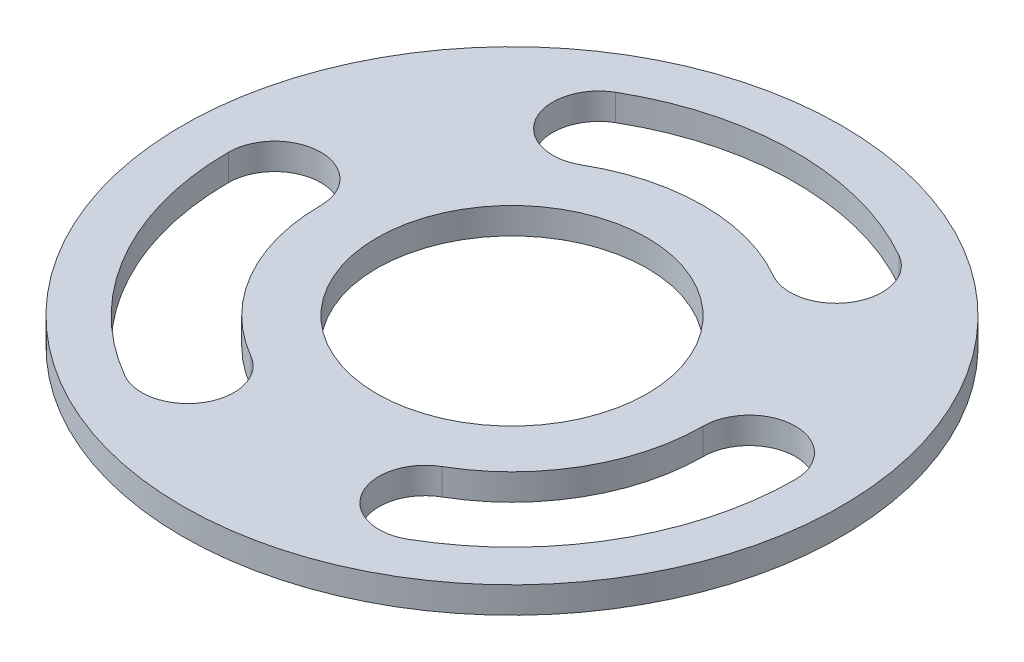
SolidWorks part; units mm, degrees
ref_plane "Alzado" through (0, 0, 0) normal (0, 0, 1) x (1, 0, 0)
ref_plane "Planta" through (0, 0, 0) normal (0, 1, 0) x (1, 0, 0)
ref_plane "Vista lateral" through (0, 0, 0) normal (1, 0, 0) x (0, 0, -1)
sketch "Croquis1" plane through (0, 0, 0) normal (0, 1, 0) x (1, 0, 0)
  line L0 (0, 0) -> (0, 12.5) construction
  line L1 (-4.5, 7.7942) -> (0, 0) construction
  line L2 (0, 0) -> (4.5, 7.7942) construction
  circle A0 centre (0, 0) radius 12.5
  circle A1 centre (0, 0) radius 5.125
  circle A2 centre (0, 0) radius 9 construction
  circle A3 centre (0, 9) radius 1.75 construction
  arc A4 (-4.5, 7.7942) -> (4.5, 7.7942) centre (0, 0) cw construction
  arc A5 (5.375, 9.3098) -> (-5.375, 9.3098) centre (0, 0) ccw
  arc A6 (3.625, 6.2787) -> (-3.625, 6.2787) centre (0, 0) ccw
  arc A7 (3.625, 6.2787) -> (5.375, 9.3098) centre (4.5, 7.7942) ccw
  arc A8 (-5.375, 9.3098) -> (-3.625, 6.2787) centre (-4.5, 7.7942) ccw
  arc A9 (9, 0) -> (4.5, -7.7942) centre (0, 0) cw construction
  arc A10 (5.375, -9.3098) -> (10.75, 0) centre (0, 0) ccw
  arc A11 (3.625, -6.2787) -> (7.25, 0) centre (0, 0) ccw
  arc A12 (3.625, -6.2787) -> (5.375, -9.3098) centre (4.5, -7.7942) ccw
  arc A13 (10.75, 0) -> (7.25, 0) centre (9, 0) ccw
  arc A14 (-4.5, -7.7942) -> (-9, 0) centre (0, 0) cw construction
  arc A15 (-10.75, 0) -> (-5.375, -9.3098) centre (0, 0) ccw
  arc A16 (-7.25, 0) -> (-3.625, -6.2787) centre (0, 0) ccw
  arc A17 (-7.25, 0) -> (-10.75, 0) centre (-9, 0) ccw
  arc A18 (-5.375, -9.3098) -> (-3.625, -6.2787) centre (-4.5, -7.7942) ccw
  point P11 (0, 9)
  point P23 (7.7942, -4.5)
  point P30 (-7.7942, -4.5)
  point P35 (0, 0)
  dimension "D1" = 10.25
  dimension "D2" = 25
  dimension "D3" = 18
  dimension "D4" = 3.5
  dimension "D5" = 60
  dimension "D6" = 3
extrude "Saliente-Extruir1" add sketch "Croquis1" along normal blind 1
